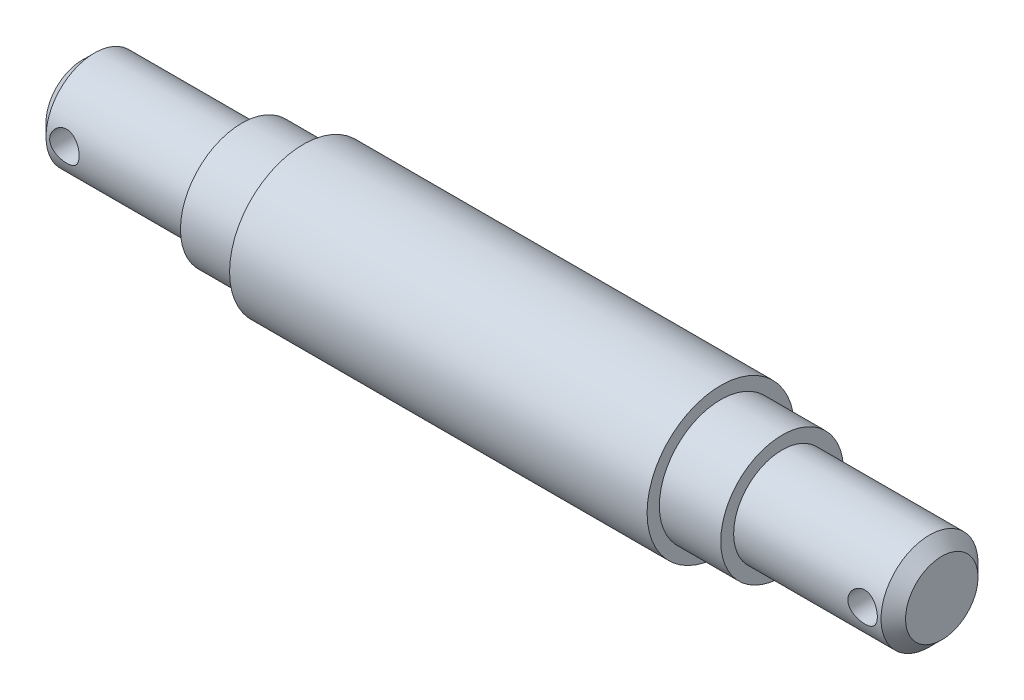
SolidWorks part; units mm, degrees
ref_plane "Front Plane" through (0, 0, 0) normal (0, 0, 1) x (1, 0, 0)
ref_plane "Top Plane" through (0, 0, 0) normal (0, 1, 0) x (1, 0, 0)
ref_plane "Right Plane" through (0, 0, 0) normal (1, 0, 0) x (0, 0, -1)
sketch "Sketch3" plane through (0, 0, 0) normal (0, 0, 1) x (1, 0, 0)
  line L0 (0, 0) -> (70, 0)
  line L1 (70, 0) -> (70, 2.95)
  line L2 (69, 3.95) -> (57, 3.95)
  line L3 (57, 3.95) -> (57, 5)
  line L4 (57, 5) -> (52, 5)
  line L5 (52, 5) -> (52, 6)
  line L6 (52, 6) -> (18, 6)
  line L7 (18, 6) -> (18, 5)
  line L8 (18, 5) -> (13, 5)
  line L9 (13, 5) -> (13, 3.95)
  line L10 (13, 3.95) -> (1, 3.95)
  line L11 (0, 2.95) -> (0, 0)
  line L12 (1, 3.95) -> (0, 2.95)
  line L13 (70, 2.95) -> (69, 3.95)
  point P3 (35, 0)
  point P4 (70, 3.95)
  point P13 (0, 3.95)
  dimension "D1" = 70
  dimension "D2" = 13
  dimension "D3" = 5
  dimension "D4" = 3.95
  dimension "D5" = 5
  dimension "D6" = 6
revolve "Revolve2" add sketch "Sketch3" angle 360 about L0
sketch "Sketch5" plane through (0, 0, 0) normal (0, 0, 1) x (1, 0, 0)
  line L0 (70, -2.95) -> (70, 2.95) construction
  circle A0 centre (2.5, 0) radius 1.2
  circle A1 centre (67.5, 0) radius 1.2
  point P7 (0, 0)
  dimension "D2" = 2.4
  dimension "D4" = 2.4
  dimension "D1" = 2.5
  dimension "D3" = 2.5
extrude "Cut-Extrude2" cut sketch "Sketch5" against normal through all both and the other way through all
